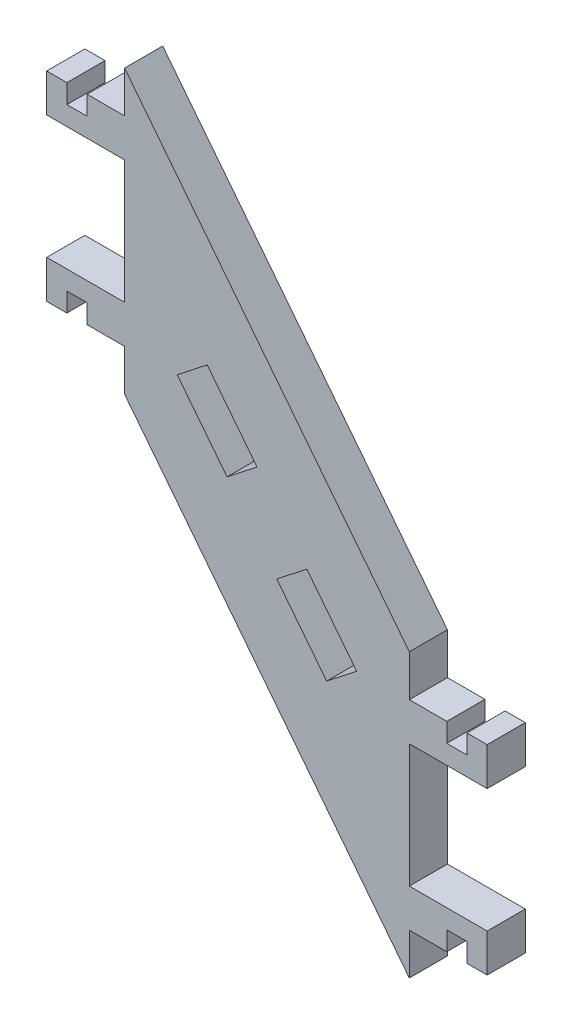
SolidWorks part; units mm, degrees
ref_plane "Front Plane" through (0, 0, 0) normal (0, 0, 1) x (1, 0, 0)
ref_plane "Top Plane" through (0, 0, 0) normal (0, 1, 0) x (1, 0, 0)
ref_plane "Right Plane" through (0, 0, 0) normal (1, 0, 0) x (0, 0, -1)
sketch "Sketch1" plane through (0, 0, 0) normal (0, 0, 1) x (1, 0, 0)
  line L0 (-44.8, 79.375) -> (-44.8, 72.85)
  line L1 (-44.8, 34.925) -> (0, -22.225)
  line L2 (0, -22.225) -> (0, -15.7)
  line L3 (0, 22.225) -> (-44.8, 79.375)
  line L4 (-44.8, 72.85) -> (-50.7, 72.85)
  line L5 (-57.05, 72.85) -> (-57.05, 66.85)
  line L6 (-57.05, 66.85) -> (-44.8, 66.85)
  line L7 (-44.8, 79.375) -> (-50.7, 79.375) construction
  line L8 (-50.7, 79.375) -> (-50.7, 34.925) construction
  line L9 (-50.7, 34.925) -> (-44.8, 34.925) construction
  line L10 (-53.875, 72.85) -> (-53.875, 69.85)
  line L11 (-53.875, 69.85) -> (-50.7, 69.85)
  line L12 (-50.7, 69.85) -> (-50.7, 72.85)
  line L13 (-53.875, 72.85) -> (-57.05, 72.85)
  line L14 (-44.8, 57.15) -> (-64.1486, 57.15) construction
  line L15 (-44.8, 41.45) -> (-50.7, 41.45)
  line L16 (-57.05, 47.45) -> (-44.8, 47.45)
  line L17 (-53.875, 41.45) -> (-57.05, 41.45)
  line L18 (-50.7, 44.45) -> (-50.7, 41.45)
  line L19 (-53.875, 44.45) -> (-50.7, 44.45)
  line L20 (-53.875, 41.45) -> (-53.875, 44.45)
  line L21 (-57.05, 41.45) -> (-57.05, 47.45)
  line L22 (-57.05, 69.85) -> (-50.7, 69.85) construction
  line L23 (0, 0) -> (19.05, 0) construction
  line L24 (0, 9.7) -> (12.25, 9.7)
  line L25 (12.25, 9.7) -> (12.25, 15.7)
  line L26 (12.25, 15.7) -> (9.075, 15.7)
  line L27 (9.075, 15.7) -> (9.075, 12.7)
  line L28 (9.075, 12.7) -> (5.9, 12.7)
  line L29 (5.9, 12.7) -> (5.9, 15.7)
  line L30 (5.9, 15.7) -> (0, 15.7)
  line L31 (5.9, -15.7) -> (0, -15.7)
  line L32 (5.9, -12.7) -> (5.9, -15.7)
  line L33 (9.075, -12.7) -> (5.9, -12.7)
  line L34 (9.075, -15.7) -> (9.075, -12.7)
  line L35 (12.25, -15.7) -> (9.075, -15.7)
  line L36 (12.25, -9.7) -> (12.25, -15.7)
  line L37 (0, -9.7) -> (12.25, -9.7)
  line L38 (0, 22.225) -> (5.9, 22.225) construction
  line L39 (5.9, 22.225) -> (5.9, -22.225) construction
  line L40 (5.9, -22.225) -> (0, -22.225) construction
  line L41 (-44.8, 41.45) -> (-44.8, 47.45) construction
  line L42 (-44.8, 66.85) -> (-44.8, 47.45)
  line L43 (-44.8, 41.45) -> (-44.8, 34.925)
  line L44 (0, 15.7) -> (0, 22.225)
  line L45 (0, -9.7) -> (0, 9.7)
  line L46 (-50.8, -31.2865) -> (-44.8, -31.2865) construction
  line L47 (-50.8, -31.2865) -> (-50.8, 31.2865) construction
  line L48 (-50.8, 31.2865) -> (-44.8, 31.2865) construction
  line L49 (-44.8, -31.2865) -> (-44.8, 31.2865) construction
  line L50 (-50.8, -31.2865) -> (-44.8, 31.2865) construction
  line L51 (-50.8, 31.2865) -> (-44.8, -31.2865) construction
  line L52 (0, -31.2865) -> (6, -31.2865) construction
  line L53 (0, -31.2865) -> (0, 31.2865) construction
  line L54 (0, 31.2865) -> (6, 31.2865) construction
  line L55 (6, -31.2865) -> (6, 31.2865) construction
  line L56 (0, -31.2865) -> (6, 31.2865) construction
  line L57 (0, 31.2865) -> (6, -31.2865) construction
  line L58 (-44.8, 66.85) -> (-44.8, 72.85) construction
  point P25 (-47.8, 0)
  point P37 (0, 0)
  point P53 (3, 0)
  point P58 (-44.8, 44.45)
  point P59 (-44.8, 69.85)
  point P60 (12.25, 12.7)
  point P61 (12.25, -12.7)
  dimension "D2" = 101.6
  dimension "D4" = 5.9
  dimension "D5" = 3.175
  dimension "D6" = 6
  dimension "D8" = 44.45
  dimension "D10" = 6
  dimension "D11" = 5.9
  dimension "D12" = 3.175
  dimension "D13" = 31.4
  dimension "D14" = 3.175
  dimension "D9" = 3.175
  dimension "D18" = 3.175
  dimension "D19" = 6
  dimension "D20" = 6
  dimension "D21" = 50.8
  dimension "D7" = 25.4
  dimension "D3" = 25.4
  dimension "D15" = 3
  dimension "D16" = 3
extrude "Profile" add sketch "Sketch1" along normal blind 6 contours L1 L2 L31 L32 L33 L34 L35 L36 L37 L45 L24 L25 L26 L27 L28 L29 L30 L44 L3 L0 L4 L12 L11 L10 L13 L5 L6 L42 L16 L21 L17 L20 L19 L18 L15 L43
sketch "Sketch2" plane through (0, 0, 6) normal (0, 0, 1) x (1, 0, 0)
  line L0 (-44.8, 57.15) -> (0, 0) construction
  line L1 (-44.8, 66.85) -> (-44.8, 47.45) construction
  line L2 (-31.7917, 45.4184) -> (-36.5137, 41.7167)
  line L3 (-36.5137, 41.7167) -> (-28.6786, 31.7217)
  line L4 (-28.6786, 31.7217) -> (-23.9565, 35.4233)
  line L5 (-23.9565, 35.4233) -> (-31.7917, 45.4184)
  line L6 (-33.1911, 20.1159) -> (-11.6089, 37.0341) construction
  line L7 (0, 22.225) -> (-44.8, 79.375) construction
  line L8 (-16.1214, 25.4283) -> (-8.2863, 15.4333)
  line L9 (-20.8435, 21.7267) -> (-16.1214, 25.4283)
  line L10 (-13.0083, 11.7316) -> (-20.8435, 21.7267)
  line L11 (-8.2863, 15.4333) -> (-13.0083, 11.7316)
  line L12 (-36.5137, 41.7167) -> (-23.9565, 35.4233) construction
  point P7 (-34.1527, 43.5676)
  point P14 (-22.4, 28.575)
  point P19 (0, 0)
  point P21 (-30.2351, 38.57)
  dimension "D1" = 6
  dimension "D2" = 12.7
  dimension "D3" = 12.7
extrude "Cut-Extrude1" cut sketch "Sketch2" against normal through all
equation "\"D10@Sketch1\"=\"D6@Sketch1\""
equation "\"D12@Sketch1\"=\"D5@Sketch1\""
equation "\"D18@Sketch1\"=\"D9@Sketch1\""
equation "\"D4@Sketch1\"=6mm-.1mm"
equation "\"D3@Sketch1\"=\"D7@Sketch1\""
equation "\"D11@Sketch1\"=\"D4@Sketch1\""
equation "\"D15@Sketch1\"=\"D16@Sketch1\""
